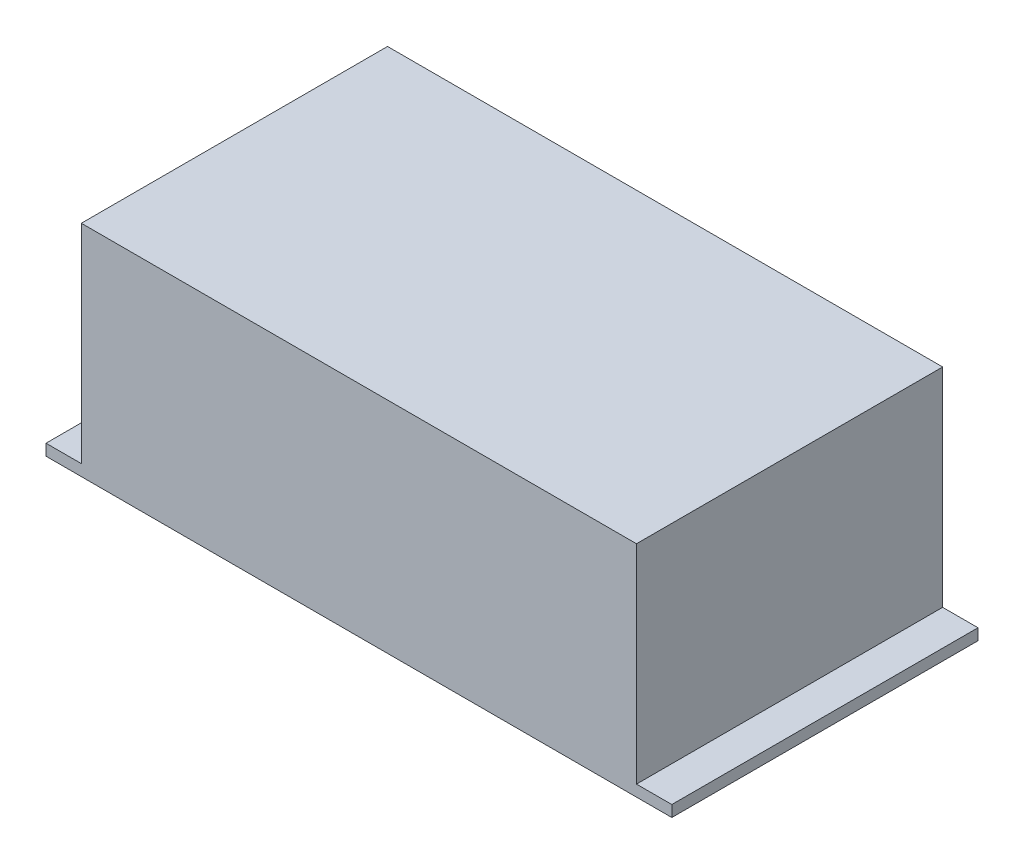
SolidWorks part; units mm, degrees
ref_plane "Front Plane" through (0, 0, 0) normal (0, 0, 1) x (1, 0, 0)
ref_plane "Top Plane" through (0, 0, 0) normal (0, 1, 0) x (1, 0, 0)
ref_plane "Right Plane" through (0, 0, 0) normal (1, 0, 0) x (0, 0, -1)
sketch "Sketch1" plane through (0, 0, 0) normal (0, 1, 0) x (1, 0, 0)
  line L1 (0, 0) -> (72.15, 0)
  line L2 (0, 0) -> (0, -35.3)
  line L3 (0, -35.3) -> (72.15, -35.3)
  line L4 (72.15, 0) -> (72.15, -35.3)
  dimension "D1" = 35.3
  dimension "D2" = 72.15
extrude "Boss-Extrude1" add sketch "Sketch1" along normal blind 1.3
sketch "Sketch2" plane through (0, 1.3, 0) normal (0, 1, 0) x (1, 0, 0)
  line L0 (0, -35.3) -> (72.15, -35.3) construction
  line L1 (68.075, -35.3) -> (4.075, -35.3)
  line L2 (68.075, -35.3) -> (68.075, 0)
  line L3 (68.075, 0) -> (4.075, 0)
  line L4 (4.075, -35.3) -> (4.075, 0)
  line L5 (72.15, 0) -> (0, 0) construction
  line L6 (36.075, 0) -> (36.075, -35.3) construction
  dimension "D1" = 64
extrude "Boss-Extrude2" add sketch "Sketch2" along normal blind 24
